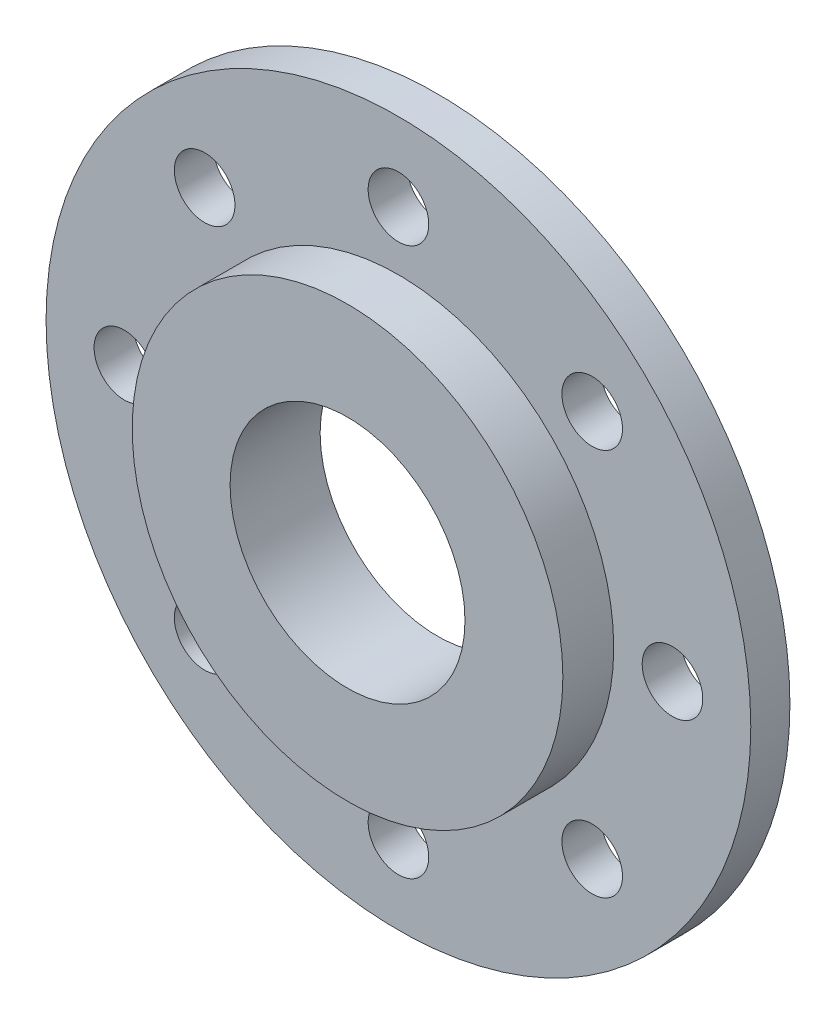
SolidWorks part; units mm, degrees
ref_plane "Front Plane" through (0, 0, 0) normal (0, 0, 1) x (1, 0, 0)
ref_plane "Top Plane" through (0, 0, 0) normal (0, 1, 0) x (1, 0, 0)
ref_plane "Right Plane" through (0, 0, 0) normal (1, 0, 0) x (0, 0, -1)
sketch "Sketch1" plane through (0, 0, 0) normal (0, 0, 1) x (1, 0, 0)
  circle A0 centre (0, 0) radius 17.4625
  dimension "D1" = 34.925
extrude "Boss-Extrude1" add sketch "Sketch1" along normal blind 4.1275
sketch "Sketch2" plane through (0, 0, 0) normal (0, 0, -1) x (-1, 0, 0)
  circle A0 centre (0, 0) radius 28.575
  dimension "D1" = 57.15
extrude "Boss-Extrude2" add sketch "Sketch2" along normal blind 3.175
hole_wizard "#10 (0.1935) Diameter Hole1" positions "Sketch3" profile "Sketch4" hole size "#10" standard "ANSI Inch" end condition through all
sketch "Sketch3" plane through (0, 0, -3.175) normal (0, 0, -1) x (-1, 0, 0)
  point P0 (0, 22.225)
  dimension "D1" = 22.225
sketch "Sketch4" plane through (0, 22.225, -3.175) normal (1, 0, 0) x (0, 1, 0)
  line L0 (0, 0) -> (0, 7.3025)
  line L1 (0, 7.3025) -> (2.4574, 7.3025)
  line L2 (2.4574, 7.3025) -> (2.4574, 0)
  line L5 (2.4574, 0) -> (0, 0)
  line L11 (0, -6.35) -> (0, 107.95) construction
  dimension "Thru Hole Dia." = 4.9149
  dimension "Thru Hole Depth" = 7.3025
pattern_circular "CirPattern1" count 8 over 360 about axis through (0, 0, 0) along (0, 0, 1) of "#10 (0.1935) Diameter Hole1"
sketch "Sketch5" plane through (0, 0, -3.175) normal (0, 0, -1) x (-1, 0, 0)
  circle A0 centre (0, 0) radius 9.525
  dimension "D1" = 19.05
extrude "Cut-Extrude1" cut sketch "Sketch5" against normal up to next
